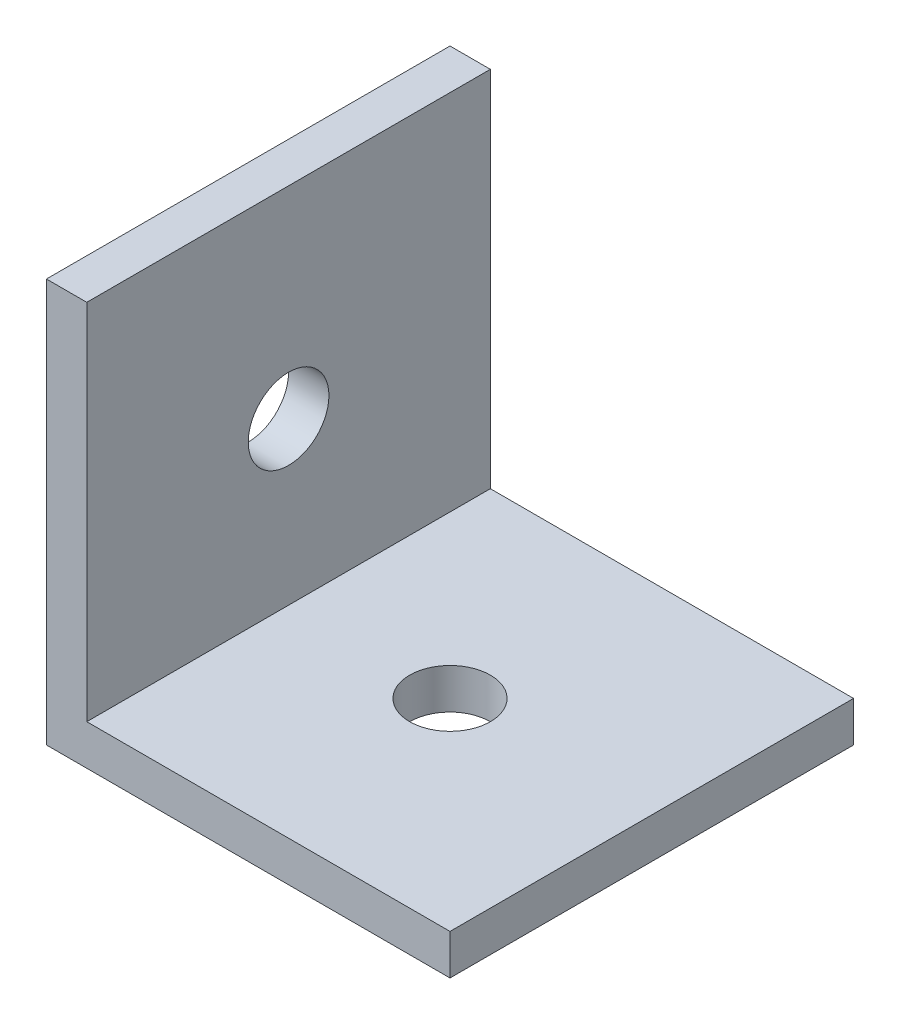
SolidWorks part; units mm, degrees
ref_plane "Plan de face" through (0, 0, 0) normal (0, 0, 1) x (1, 0, 0)
ref_plane "Plan de dessus" through (0, 0, 0) normal (0, 1, 0) x (1, 0, 0)
ref_plane "Plan de droite" through (0, 0, 0) normal (1, 0, 0) x (0, 0, -1)
sketch "Esquisse1" plane through (0, 0, 0) normal (0, 0, 1) x (1, 0, 0)
  line L0 (-27.4313, 3.8641) -> (-27.4313, -11.1359)
  line L1 (-27.4313, -11.1359) -> (-12.4313, -11.1359)
  line L2 (-12.4313, -11.1359) -> (-12.4313, -9.6359)
  line L3 (-12.4313, -9.6359) -> (-25.9313, -9.6359)
  line L4 (-25.9313, -9.6359) -> (-25.9313, 3.8641)
  line L5 (-25.9313, 3.8641) -> (-27.4313, 3.8641)
  dimension "D1" = 1.5
  dimension "D2" = 1.5
  dimension "D3" = 15
  dimension "D4" = 15
extrude "Extrusion1" add sketch "Esquisse1" along normal blind 15
sketch "Esquisse2" plane through (-25.9313, 0, 0) normal (1, 0, 0) x (0, 0, -1)
  line L0 (-15, 3.8641) -> (0, 3.8641) construction
  line L1 (0, -9.6359) -> (0, 3.8641) construction
  circle A0 centre (-7.5, -3.6359) radius 1.5
  dimension "D1" = 7.5
  dimension "D2" = 7.5
extrude "Extrusion2" cut sketch "Esquisse2" against normal blind 15
sketch "Esquisse3" plane through (0, -9.6359, 0) normal (0, 1, 0) x (-1, 0, 0)
  line L0 (12.4313, 0) -> (25.9313, 0) construction
  line L1 (12.4313, 15) -> (12.4313, 0) construction
  circle A0 centre (19.9313, 7.5) radius 1.5
  point P4 (12.4313, 7.5)
  dimension "D1" = 7.5
  dimension "D2" = 7.5
extrude "Extrusion3" cut sketch "Esquisse3" against normal blind 15
